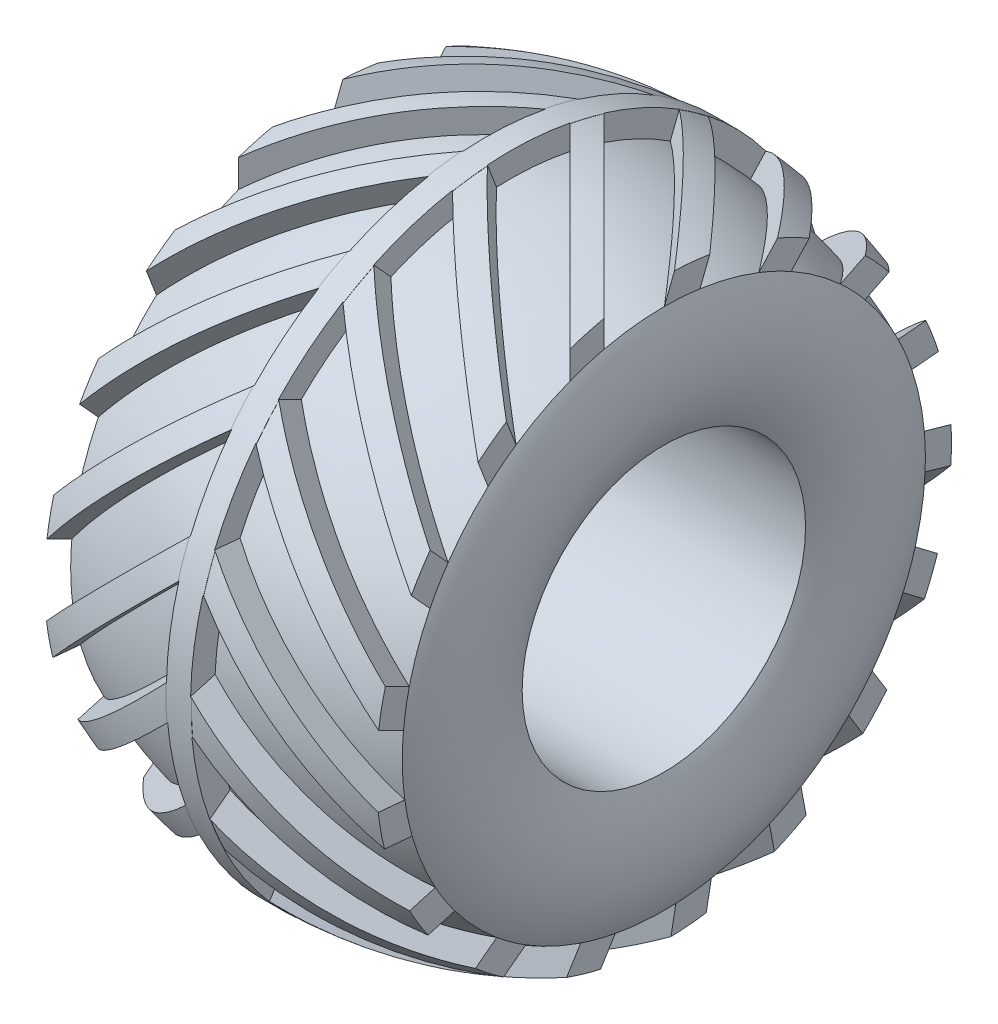
SolidWorks part; units mm, degrees
material "Rubber"
ref_plane "Front Plane" through (0, 0, 0) normal (0, 0, 1) x (1, 0, 0)
ref_plane "Top Plane" through (0, 0, 0) normal (0, 1, 0) x (1, 0, 0)
ref_plane "Right Plane" through (0, 0, 0) normal (1, 0, 0) x (0, 0, -1)
sketch "Sketch1" plane through (0, 0, 0) normal (0, 0, 1) x (1, 0, 0)
  line L0 (0, 0) -> (41.3801, 0) construction
  line L1 (-27.5, 23.5) -> (27.5, 23.5)
  line L2 (0, 23.5) -> (0, 0) construction
  line L3 (-27.5, 43.372) -> (27.5, 43.372) construction
  line L4 (-27.5, 23.5) -> (-27.5, -27.6884) construction
  line L5 (0, 43.372) -> (0, 23.5) construction
  line L6 (0, 43.372) -> (0, 91.8051) construction
  line L7 (-2, 53) -> (2, 53)
  line L8 (2, 53) -> (2, 48.9714)
  line L10 (-2, 48.9714) -> (-2, 53)
  arc A0 (27.5, 43.372) -> (27.5, 23.5) centre (9.0052, 33.436) cw
  arc A1 (-27.5, 43.372) -> (-2, 48.9714) centre (0, -21) cw
  arc A2 (-27.5, 43.372) -> (-27.5, 23.5) centre (-9.0052, 33.436) ccw
  arc A3 (2, 48.9714) -> (27.5, 43.372) centre (0, -21) cw
  point P17 (0, 53)
  dimension "D3" = 49
  dimension "D4" = 60
  dimension "D5" = 55
  dimension "D6" = 70
  dimension "D1" = 55
  dimension "D2" = 23.5
  dimension "D7" = 4
  dimension "D8" = 4
revolve "Revolve1" add sketch "Sketch1" angle 360 about L0
ref_plane "Plane1" through (0, 30, 0) normal (0, 1, 0) x (1, 0, 0)
sketch "Sketch2" plane through (0, 30, 0) normal (0, 1, 0) x (1, 0, 0)
  line L0 (0, 0) -> (54.0828, 0) construction
  line L1 (2, 15.5784) -> (27.5, -9.9216)
  line L2 (2, -48.9714) -> (2, 48.9714) construction
  line L3 (27.5, -43.372) -> (27.5, 43.372) construction
  line L4 (27.5, -9.9216) -> (27.5, -15.5784)
  line L5 (27.5, -15.5784) -> (2, 9.9216)
  line L6 (2, 9.9216) -> (2, 15.5784)
  line L7 (2, 15.5784) -> (2, 0) construction
  line L8 (27.5, -15.5784) -> (27.5, 0) construction
  line L9 (0, 0) -> (0, 60.4891) construction
  line L10 (-27.5, -15.5784) -> (-27.5, 0) construction
  line L11 (-2, 15.5784) -> (-2, 0) construction
  line L12 (0, 0) -> (-54.0828, 0) construction
  line L13 (-2, 9.9216) -> (-2, 15.5784)
  line L14 (-27.5, -15.5784) -> (-2, 9.9216)
  line L15 (-27.5, -9.9216) -> (-27.5, -15.5784)
  line L16 (-2, 15.5784) -> (-27.5, -9.9216)
  dimension "D1" = 4
  dimension "D2" = 45
extrude "Boss-Extrude1" add sketch "Sketch2" along normal up to surface (22.0631 mm away)
pattern_circular "CirPattern1" count 17 over 360 about axis through (0, 0, 0) along (1, 0, 0) of "Boss-Extrude1"
sketch "Sketch3" plane through (0, 0, 0) normal (0, 0, 1) x (1, 0, 0)
  line L0 (-29.0714, 47.0504) -> (-29.0714, 58.2289)
  line L1 (-29.0714, 58.2289) -> (-2.1143, 58.2289)
  line L2 (-2.1143, 58.2289) -> (-2.1143, 52.9698)
  line L3 (2.1143, 52.9698) -> (2.1143, 58.2289)
  line L4 (2.1143, 58.2289) -> (29.0714, 58.2289)
  line L5 (29.0714, 58.2289) -> (29.0714, 47.0504)
  line L6 (-200000, 0) -> (200041.3801, 0) construction
  line L7 (-200000, 0) -> (200041.3801, 0) construction
  arc A0 (27.5, 43.372) -> (2, 48.9714) centre (0, -21) ccw construction
  arc A1 (-2, 48.9714) -> (-27.5, 43.372) centre (0, -21) ccw construction
  arc A2 (-2, 48.9714) -> (-27.5, 43.372) centre (0, -21) ccw construction
  arc A3 (27.5, 43.372) -> (2, 48.9714) centre (0, -21) ccw construction
  arc A4 (-2.1143, 52.9698) -> (-29.0714, 47.0504) centre (0, -21) ccw
  arc A5 (29.0714, 47.0504) -> (2.1143, 52.9698) centre (0, -21) ccw
  dimension "D1" = 4
revolve "Cut-Revolve1" cut sketch "Sketch3" angle 360 about L7
